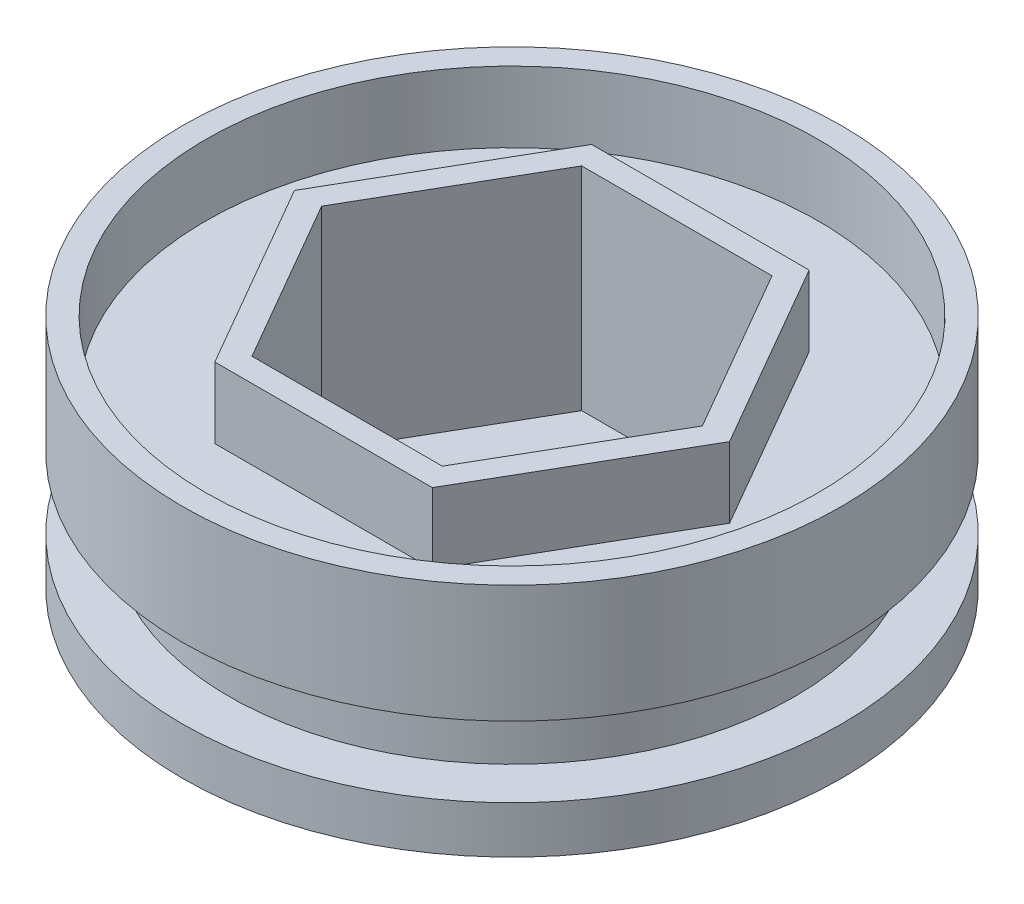
SolidWorks part; units mm, degrees
material "ABS"
ref_plane "Front" through (0, 0, 0) normal (0, 0, 1) x (1, 0, 0)
ref_plane "Top" through (0, 0, 0) normal (0, 1, 0) x (1, 0, 0)
ref_plane "Right" through (0, 0, 0) normal (1, 0, 0) x (0, 0, -1)
sketch "Sketch1" plane through (0, 0, 0) normal (0, 1, 0) x (1, 0, 0)
  circle A0 centre (0, 0) radius 14
extrude "Boss-Extrude1" add sketch "Sketch1" along normal blind 10
sketch "Sketch2" plane through (0, 10, 0) normal (0, 1, 0) x (1, 0, 0)
  circle A0 centre (0, 0) radius 13
  circle A1 centre (0, 0) radius 14 construction
  dimension "D1" = 1
extrude "Cut-Extrude1" cut sketch "Sketch2" against normal blind 3
sketch "Sketch3" plane through (0, 7, 0) normal (0, 1, 0) x (1, 0, 0)
  line L1 (9.2376, 0) -> (4.6188, 8)
  line L2 (4.6188, 8) -> (-4.6188, 8)
  line L3 (-4.6188, 8) -> (-9.2376, 0)
  line L4 (-9.2376, 0) -> (-4.6188, -8)
  line L5 (-4.6188, -8) -> (4.6188, -8)
  line L6 (4.6188, -8) -> (9.2376, 0)
  circle A0 centre (0, 0) radius 8 construction
extrude "Boss-Extrude2" add sketch "Sketch3" along normal blind 3
sketch "Sketch4" plane through (0, 10, 0) normal (0, 1, 0) x (1, 0, 0)
  line L1 (8.0829, 0) -> (4.0415, 7)
  line L2 (4.0415, 7) -> (-4.0415, 7)
  line L3 (-4.0415, 7) -> (-8.0829, 0)
  line L4 (-8.0829, 0) -> (-4.0415, -7)
  line L5 (-4.0415, -7) -> (4.0415, -7)
  line L6 (4.0415, -7) -> (8.0829, 0)
  circle A0 centre (0, 0) radius 7 construction
extrude "Cut-Extrude2" cut sketch "Sketch4" against normal blind 9
sketch "Sketch5" plane through (0, 0, 0) normal (0, 0, 1) x (1, 0, 0)
  line L0 (14, 0) -> (14, 10) construction
  line L1 (14, 2) -> (12, 2)
  line L2 (14, 2) -> (14, 5)
  line L3 (14, 5) -> (12, 5)
  line L4 (12, 2) -> (12, 5)
  line L5 (13, 5) -> (13, 2) construction
  line L6 (14, 3.5) -> (12, 3.5) construction
  line L7 (-14, 0) -> (14, 0) construction
  point P116 (13, 3.5)
  dimension "D1" = 3
  dimension "D2" = 2
  dimension "D3" = 2
ref_plane "Plane1" through (0, 3.5, 0) normal (0, 1, 0) x (1, 0, 0)
sketch "Sketch6" plane through (0, 3.5, 0) normal (0, 1, 0) x (1, 0, 0)
  circle A0 centre (0, 0) radius 13
sweep "Cut-Sweep1" cut profiles "Sketch5" path "Sketch6"
